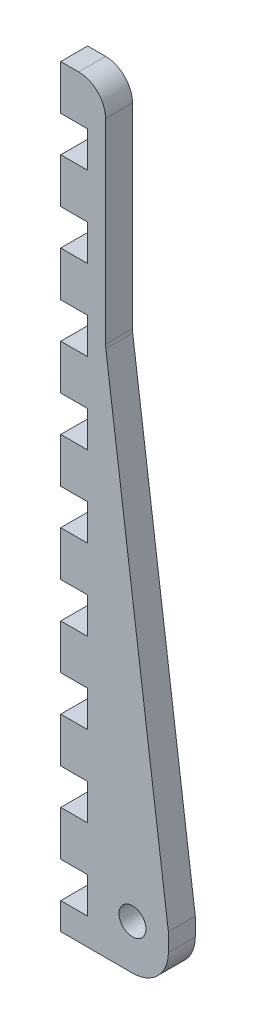
SolidWorks part; units mm, degrees
ref_plane "Front Plane" through (0, 0, 0) normal (0, 0, 1) x (1, 0, 0)
ref_plane "Top Plane" through (0, 0, 0) normal (0, 1, 0) x (1, 0, 0)
ref_plane "Right Plane" through (0, 0, 0) normal (1, 0, 0) x (0, 0, -1)
sketch "Sketch1" plane through (0, 0, 0) normal (0, 0, 1) x (1, 0, 0)
  line L0 (0, 7) -> (0, 12)
  line L1 (8, 0) -> (0, 0)
  line L2 (0, 0) -> (0, 3)
  line L3 (0, 3) -> (3, 3)
  line L4 (5.0258, 58.8044) -> (12, 6)
  line L5 (0, 30) -> (0, 25)
  line L6 (0, 12) -> (3, 12)
  line L7 (0, 7) -> (3, 7)
  line L8 (0, 16) -> (0, 21)
  line L9 (0, 16) -> (3, 16)
  line L10 (3, 7) -> (3, 3)
  line L11 (3, 12) -> (3, 16)
  line L12 (12, 6) -> (12, 4)
  line L13 (0, 21) -> (3, 21)
  line L15 (0, 25) -> (3, 25)
  line L16 (3, 21) -> (3, 25)
  line L17 (0, 30) -> (3, 30)
  line L20 (3, 30) -> (3, 34)
  line L21 (0, 84) -> (2, 84)
  line L22 (0, 84) -> (0, 79)
  line L23 (0, 34) -> (3, 34)
  line L24 (5, 81) -> (5, 59.1973)
  line L25 (0, 39) -> (3, 39)
  line L26 (0, 34) -> (0, 39)
  line L27 (0, 43) -> (3, 43)
  line L28 (3, 39) -> (3, 43)
  line L29 (0, 52) -> (3, 52)
  line L31 (0, 48) -> (3, 48)
  line L32 (3, 52) -> (3, 48)
  line L33 (0, 61) -> (3, 61)
  line L35 (0, 57) -> (3, 57)
  line L36 (3, 61) -> (3, 57)
  line L37 (0, 70) -> (3, 70)
  line L39 (0, 66) -> (3, 66)
  line L40 (3, 70) -> (3, 66)
  line L41 (0, 79) -> (3, 79)
  line L43 (0, 75) -> (3, 75)
  line L44 (3, 79) -> (3, 75)
  line L45 (0, 75) -> (0, 70)
  line L46 (0, 48) -> (0, 43)
  line L47 (0, 57) -> (0, 52)
  line L48 (0, 66) -> (0, 61)
  arc A0 (8, 0) -> (12, 4) centre (8, 4) ccw
  arc A1 (5.0258, 58.8044) -> (5, 59.1973) centre (8, 59.1973) cw
  circle A2 centre (8, 5) radius 1.5
  arc A3 (2, 84) -> (5, 81) centre (2, 81) cw
  point P11 (12, 0)
  point P50 (5, 59)
  point P53 (5, 84)
  dimension "D4" = 4
  dimension "D5" = 3
  dimension "D6" = 5
  dimension "D7" = 4
  dimension "D20" = 3
  dimension "D1" = 12
  dimension "D2" = 77
  dimension "D3" = 3
  dimension "D8" = 5
  dimension "D9" = 25
  dimension "D10" = 5
  dimension "D11" = 5
  dimension "D12" = 5
  dimension "D13" = 3
  dimension "D14" = 5
  dimension "D15" = 4
  dimension "D16" = 5
  dimension "D17" = 5
  dimension "D18" = 5
  dimension "D19" = 5
  dimension "D21" = 2
  dimension "D22" = 5
  dimension "D23" = 3
  dimension "D24" = 3
extrude "Boss-Extrude1" add sketch "Sketch1" along normal blind 3
